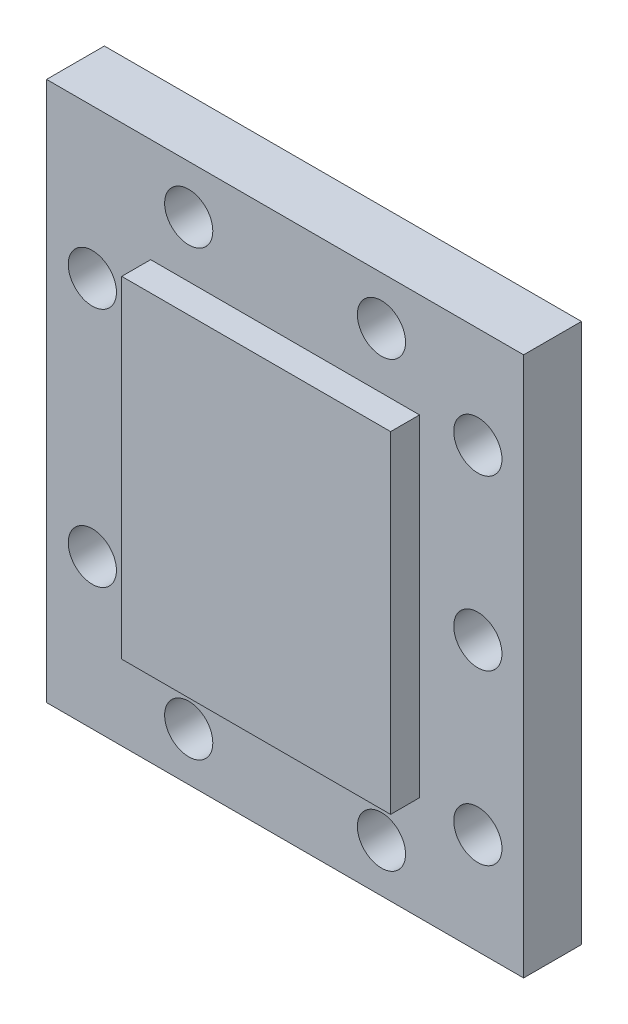
SolidWorks part; units mm, degrees
ref_plane "Front Plane" through (0, 0, 0) normal (0, 0, 1) x (1, 0, 0)
ref_plane "Top Plane" through (0, 0, 0) normal (0, 1, 0) x (1, 0, 0)
ref_plane "Right Plane" through (0, 0, 0) normal (1, 0, 0) x (0, 0, -1)
sketch "Sketch1" plane through (0, 0, 0) normal (0, 0, 1) x (1, 0, 0)
  line L1 (-31.4325, 35.56) -> (31.4325, 35.56)
  line L2 (-31.4325, 35.56) -> (-31.4325, -35.56)
  line L3 (-31.4325, -35.56) -> (31.4325, -35.56)
  line L4 (31.4325, 35.56) -> (31.4325, -35.56)
  line L5 (-31.4325, 35.56) -> (31.4325, -35.56) construction
  line L6 (-31.4325, -35.56) -> (31.4325, 35.56) construction
  point P0 (0, 0)
extrude "Boss-Extrude1" add sketch "Sketch1" along normal blind 7.62
sketch "Sketch2" plane through (0, 0, 7.62) normal (0, 0, 1) x (1, 0, 0)
  line L1 (-17.7165, 21.844) -> (17.7165, 21.844)
  line L2 (-17.7165, 21.844) -> (-17.7165, -21.844)
  line L3 (-17.7165, -21.844) -> (17.7165, -21.844)
  line L4 (17.7165, 21.844) -> (17.7165, -21.844)
  line L5 (-17.7165, 21.844) -> (17.7165, -21.844) construction
  line L6 (-17.7165, -21.844) -> (17.7165, 21.844) construction
  point P0 (0, 0)
extrude "Boss-Extrude2" add sketch "Sketch2" along normal blind 3.81
sketch "Sketch3" plane through (0, 0, 0) normal (0, 0, -1) x (-1, 0, 0)
  line L4 (17.7165, 21.844) -> (-17.7165, 21.844)
  line L5 (-17.7165, 21.844) -> (-17.7165, -21.844)
  line L6 (-17.7165, -21.844) -> (17.7165, -21.844)
  line L7 (17.7165, -21.844) -> (17.7165, 21.844)
  line L8 (17.7165, 21.844) -> (-17.7165, 21.844)
  line L9 (-17.7165, 21.844) -> (-17.7165, -21.844)
  line L10 (-17.7165, -21.844) -> (17.7165, -21.844)
  line L11 (17.7165, -21.844) -> (17.7165, 21.844)
  dimension "D1" = 0
extrude "Cut-Extrude1" cut sketch "Sketch3" against normal blind 3.175
sketch "Sketch4" plane through (0, 0, 7.62) normal (0, 0, 1) x (1, 0, 0)
  line L0 (0, 45.008) -> (0, -53.1778) construction
  line L1 (-53.0293, 0) -> (61.4961, 0) construction
  circle A0 centre (-12.7, 29.21) radius 3.175
  circle A1 centre (-25.4, 15.875) radius 3.175
  circle A2 centre (-12.7, -29.21) radius 3.175
  circle A3 centre (-25.4, -15.875) radius 3.175
  circle A4 centre (12.7, -29.21) radius 3.175
  circle A5 centre (12.7, 29.21) radius 3.175
  circle A6 centre (25.4, 0) radius 3.175
  circle A7 centre (25.4, 22.225) radius 3.175
  circle A8 centre (25.4, -22.225) radius 3.175
  dimension "D1" = 12.7
  dimension "D3" = 6.35
  dimension "D5" = 6.35
  dimension "D7" = 25.4
  dimension "D8" = 22.225
  dimension "D2" = 29.21
  dimension "D4" = 15.875
  dimension "D6" = 25.4
  dimension "D9" = 25.4
extrude "Cut-Extrude2" cut sketch "Sketch4" against normal through all both and the other way through all
